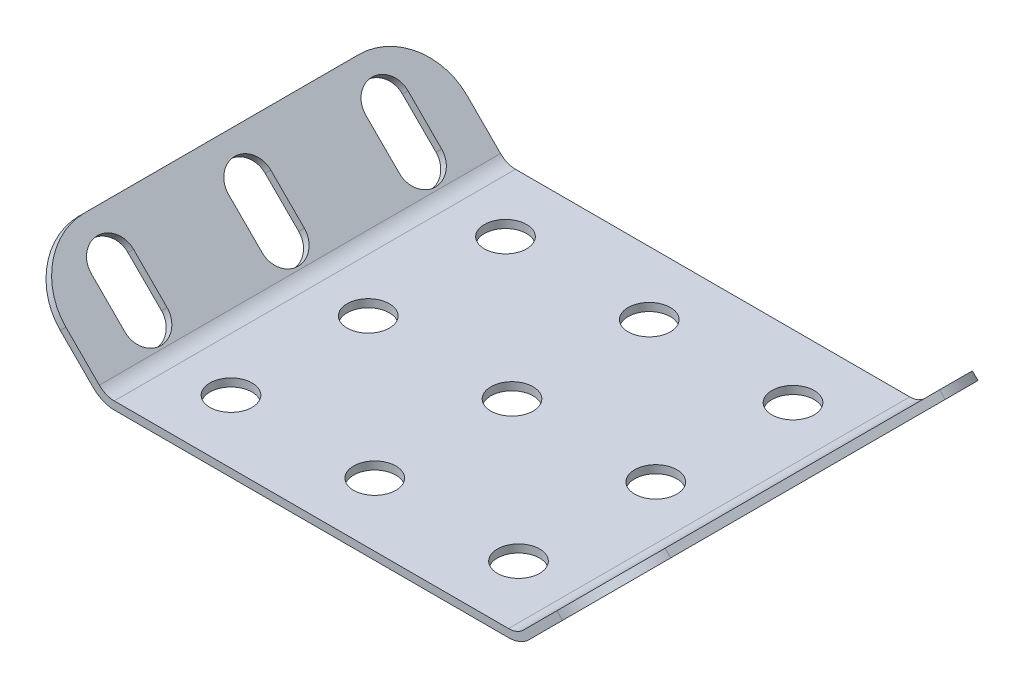
SolidWorks part; units mm, degrees
ref_plane "Piano frontale" through (0, 0, 0) normal (0, 0, 1) x (1, 0, 0)
ref_plane "Piano superiore" through (0, 0, 0) normal (0, 1, 0) x (1, 0, 0)
ref_plane "Piano destro" through (0, 0, 0) normal (1, 0, 0) x (0, 0, -1)
sketch "Schizzo1" plane through (0, 0, 0) normal (0, 0, 1) x (1, 0, 0)
  line L0 (-27.5, 8) -> (-20.0858, 0.5858)
  line L1 (-18.6716, 0) -> (0, 0)
  arc A0 (-20.0858, 0.5858) -> (-18.6716, 0) centre (-18.6716, 2) ccw
  point P6 (-19.5, 0)
  dimension "D4" = 2
  dimension "D1" = 27.5
  dimension "D2" = 45
  dimension "D3" = 8
extrude "Estrusione-Sottile1" add sketch "Schizzo1" along normal mid plane 38 thin
sketch "Schizzo2" plane through (0, -0.75, 0) normal (0, -1, 0) x (1, 0, 0)
  line L0 (0, -13) -> (-18.6716, -13) construction
  line L1 (0, 19) -> (0, -19) construction
  line L2 (-18.6716, 19) -> (-18.6716, -19) construction
  line L3 (0, 0) -> (-18.6716, 0) construction
  line L4 (0, 13) -> (-18.6716, 13) construction
  line L5 (0, 13) -> (0, 19) construction
  line L6 (0, -13) -> (0, -19) construction
  line L7 (-13.6161, -13) -> (-13.6161, -15) construction
  line L8 (-18.6716, -19) -> (0, -19) construction
  line L9 (-13.6161, -13) -> (-15.6161, -13) construction
  line L10 (-20.6161, 19) -> (-20.6161, -19) construction
  circle A0 centre (-13.6161, -13) radius 2
  circle A1 centre (0, -13) radius 2
  circle A2 centre (-13.6161, 0) radius 2
  circle A3 centre (0, 0) radius 2
  circle A4 centre (0, 13) radius 2
  circle A5 centre (-13.6161, 13) radius 2
  dimension "D1" = 4
  dimension "D2" = 4
  dimension "D3" = 5
extrude "Taglio-Estrusione2" cut sketch "Schizzo2" against normal blind 10
sketch "Schizzo3" plane through (-9.75, -9.75, 0) normal (0.7071, 0.7071, 0) x (0, 0, -1)
  line L0 (-13, 0.8839) -> (-13, 25.1023) construction
  line L1 (-19, 25.1023) -> (19, 25.1023) construction
  line L2 (-13, 21.3523) -> (-13, 16.8523) construction
  line L3 (-11, 21.3523) -> (-11, 16.8523)
  line L4 (-15, 21.3523) -> (-15, 16.8523)
  line L5 (0, 21.3523) -> (0, 16.8523) construction
  line L6 (2, 21.3523) -> (2, 16.8523)
  line L7 (-2, 21.3523) -> (-2, 16.8523)
  line L8 (13, 16.8523) -> (13, 21.3523) construction
  line L9 (11, 16.8523) -> (11, 21.3523)
  line L10 (15, 16.8523) -> (15, 21.3523)
  arc A0 (-11, 21.3523) -> (-15, 21.3523) centre (-13, 21.3523) ccw
  arc A1 (-15, 16.8523) -> (-11, 16.8523) centre (-13, 16.8523) ccw
  arc A2 (2, 21.3523) -> (-2, 21.3523) centre (0, 21.3523) ccw
  arc A3 (-2, 16.8523) -> (2, 16.8523) centre (0, 16.8523) ccw
  arc A4 (11, 16.8523) -> (15, 16.8523) centre (13, 16.8523) ccw
  arc A5 (15, 21.3523) -> (11, 21.3523) centre (13, 21.3523) ccw
  ellipse E0 centre (-13, -0.5303) end of major axis (-15, -0.5303) minor radius 1.4142 (-11, -0.5303) -> (-15, -0.5303) ccw construction
  ellipse E1 centre (-13, -0.5303) end of major axis (-15, -0.5303) minor radius 1.4142 (-11, -0.5303) -> (-15, -0.5303) ccw construction
  ellipse E3 centre (13, -0.5303) end of major axis (11, -0.5303) minor radius 1.4142 (15, -0.5303) -> (11, -0.5303) ccw construction
  point P17 (-13, 19.1023)
  point P22 (0, 19.1023)
  point P23 (-13, 23.3523)
  point P24 (-13, 14.8523)
  point P32 (13, 19.1023)
  point P39 (0, 0)
  dimension "D1" = 1.75
  dimension "D2" = 8.5
extrude "Taglio-Estrusione3" cut sketch "Schizzo3" against normal blind 10
fillet "Raccordo1" radius 6 2 edges at (-27.7652, 7.7348, -19) (-27.7652, 7.7348, 19)
mirror "Specchia1" about plane through (0, 0, 19) normal (1, 0, 0) of bodies 104
